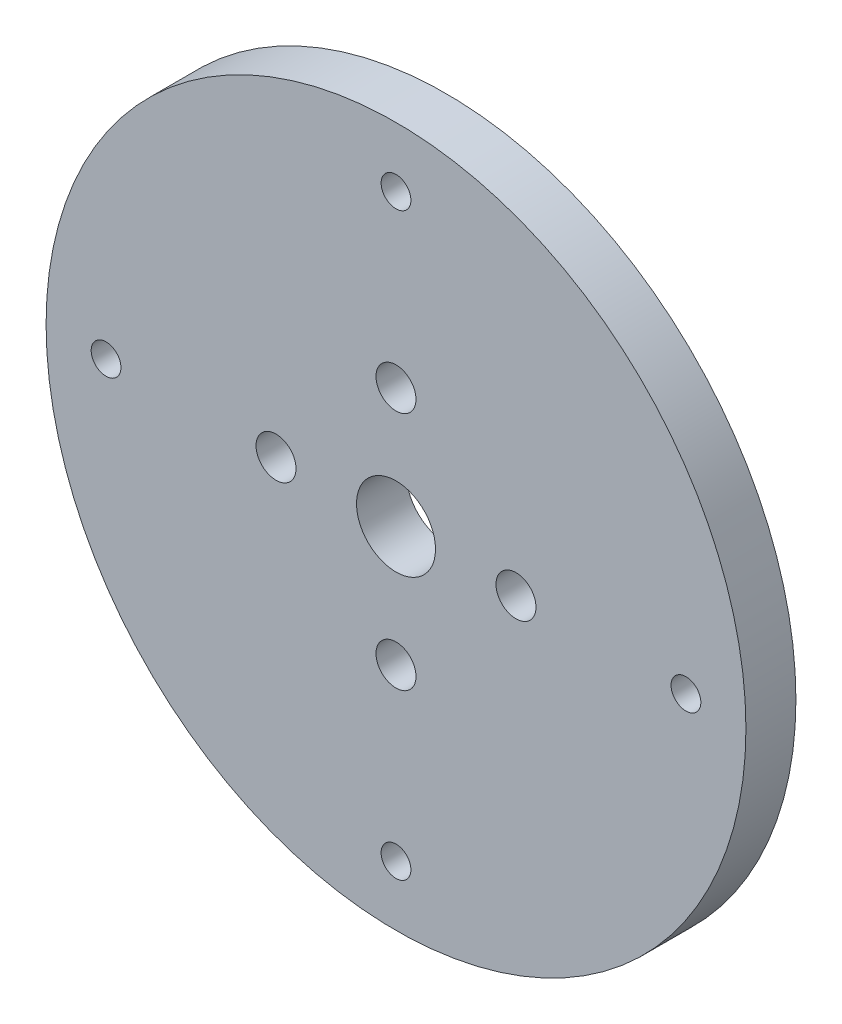
SolidWorks part; units mm, degrees
ref_plane "Front Plane" through (0, 0, 0) normal (0, 0, 1) x (1, 0, 0)
ref_plane "Top Plane" through (0, 0, 0) normal (0, 1, 0) x (1, 0, 0)
ref_plane "Right Plane" through (0, 0, 0) normal (1, 0, 0) x (0, 0, -1)
sketch "Sketch1" plane through (0, 0, 0) normal (0, 0, 1) x (1, 0, 0)
  line L0 (0, 0) -> (-29, 0) construction
  line L1 (0, 0) -> (29, 0) construction
  line L2 (0, 0) -> (0, 29) construction
  line L3 (0, 0) -> (0, -29) construction
  line L4 (0, 0) -> (12, 0) construction
  line L5 (0, 0) -> (0, 12) construction
  line L6 (0, 0) -> (-12, 0) construction
  line L7 (0, 0) -> (0, -12) construction
  circle A0 centre (0, 0) radius 35
  circle A1 centre (0, 0) radius 3.95
  circle A2 centre (-29, 0) radius 1.49
  circle A3 centre (29, 0) radius 1.49
  circle A4 centre (0, 29) radius 1.49
  circle A5 centre (0, -29) radius 1.49
  circle A6 centre (0, 12) radius 2
  circle A7 centre (12, 0) radius 2
  circle A8 centre (0, -12) radius 2
  circle A9 centre (-12, 0) radius 2
  dimension "D1" = 70
  dimension "D2" = 7.9
  dimension "D3" = 2.98
  dimension "D4" = 2.98
  dimension "D5" = 2.98
  dimension "D6" = 2.98
  dimension "D11" = 4
  dimension "D12" = 4
  dimension "D13" = 4
  dimension "D14" = 4
  dimension "D7" = 29
  dimension "D8" = 29
  dimension "D9" = 29
  dimension "D10" = 29
extrude "Boss-Extrude1" add sketch "Sketch1" along normal blind 5
